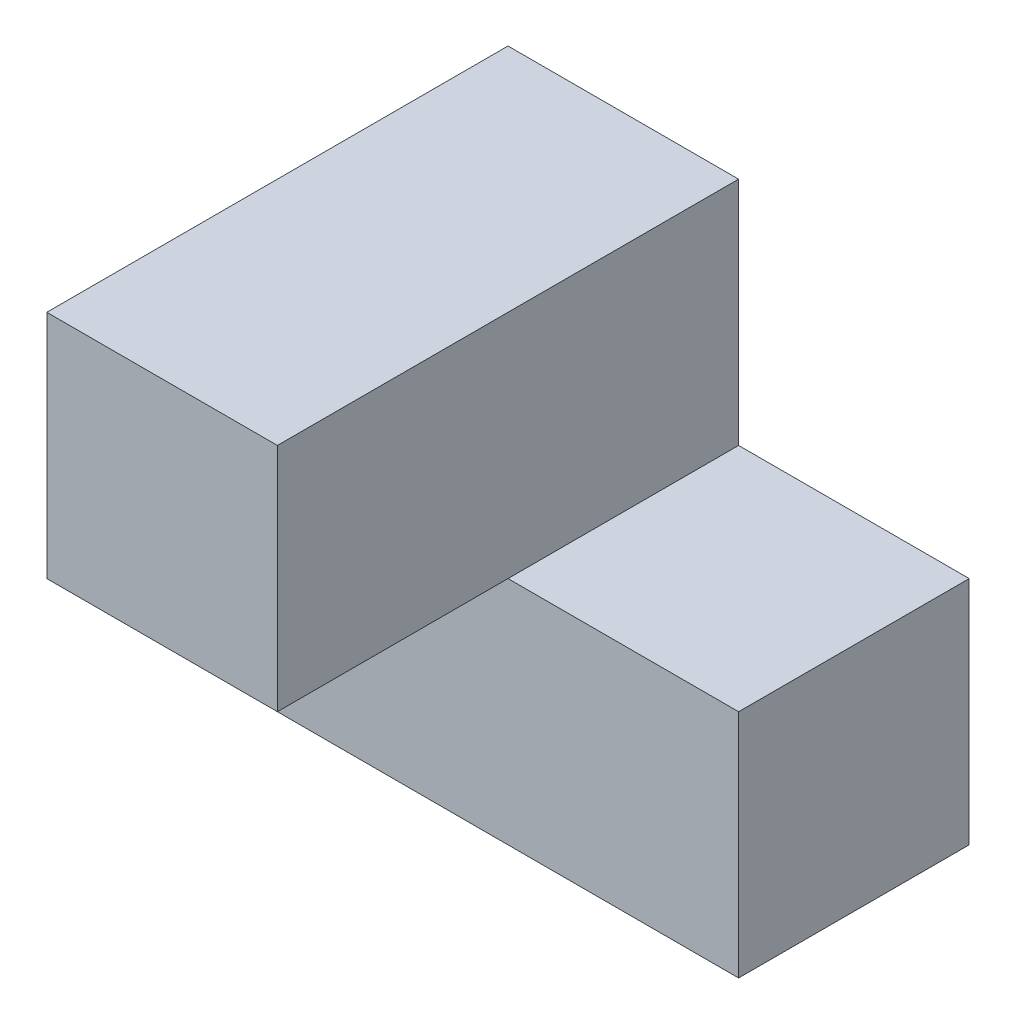
SolidWorks part; units mm, degrees
ref_plane "Plan de face" through (0, 0, 0) normal (0, 0, 1) x (1, 0, 0)
ref_plane "Plan de dessus" through (0, 0, 0) normal (0, 1, 0) x (1, 0, 0)
ref_plane "Plan de droite" through (0, 0, 0) normal (1, 0, 0) x (0, 0, -1)
sketch "Esquisse1" plane through (0, 0, 0) normal (0, 0, 1) x (1, 0, 0)
  line L1 (0, 0) -> (20, 0)
  line L2 (0, 0) -> (0, 10)
  line L3 (0, 10) -> (20, 10)
  line L4 (20, 0) -> (20, 10)
  line L5 (0, 10) -> (10, 10)
  line L6 (0, 10) -> (10, 10)
  dimension "D1" = 20
  dimension "D2" = 10
extrude "Boss.-Extru.1" add sketch "Esquisse1" against normal blind 10 contours L1 L4 L3 L2
sketch "Esquisse2" plane through (0, 0, -10) normal (0, 0, -1) x (-1, 0, 0)
  line L1 (0, 10) -> (-10, 10)
  line L2 (0, 10) -> (0, 20)
  line L3 (0, 20) -> (-10, 20)
  line L4 (-10, 10) -> (-10, 20)
  dimension "D1" = 10
  dimension "D2" = 10
extrude "Boss.-Extru.2" add sketch "Esquisse2" against normal blind 20
